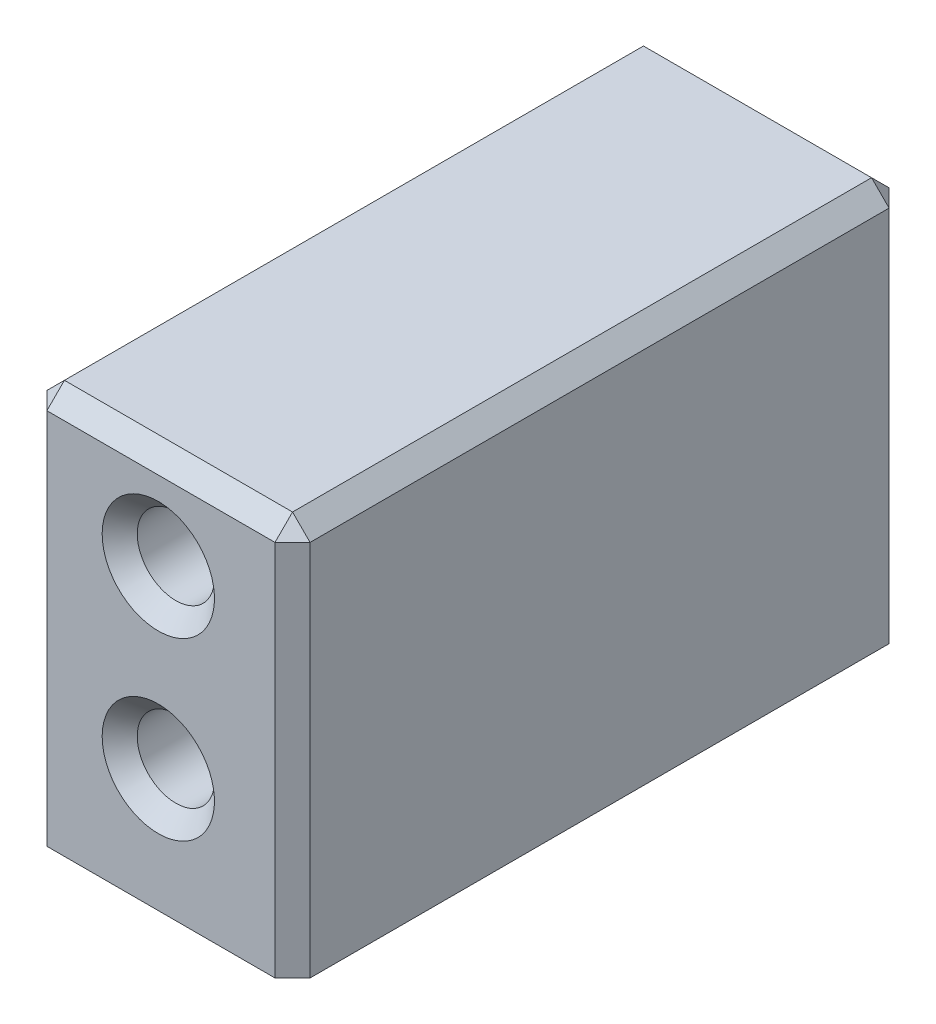
SolidWorks part; units mm, degrees
ref_plane "Front Plane" through (0, 0, 0) normal (0, 0, 1) x (1, 0, 0)
ref_plane "Top Plane" through (0, 0, 0) normal (0, 1, 0) x (1, 0, 0)
ref_plane "Right Plane" through (0, 0, 0) normal (1, 0, 0) x (0, 0, -1)
sketch "Sketch1" plane through (0, 0, 0) normal (0, 1, 0) x (1, 0, 0)
  line L0 (-41.5745, 21.3069) -> (-41.5745, -23.1431)
  line L9 (-41.5745, -23.1431) -> (-22.5245, -23.1431)
  line L10 (-22.5245, -23.1431) -> (-22.5245, 21.3069)
  line L11 (-22.5245, 21.3069) -> (-41.5745, 21.3069)
  dimension "D1" = 44.45
  dimension "D2" = 19.05
extrude "Boss-Extrude1" add sketch "Sketch1" along normal blind 28.575
sketch "Sketch3" plane through (0, 0, 23.1431) normal (0, 0, 1) x (1, 0, 0)
  line L1 (-41.5745, 0) -> (-22.5245, 0) construction
  line L3 (-41.5745, 28.575) -> (-41.5745, 0) construction
  circle A3 centre (-32.24, 34.29) radius 2.794
  circle A4 centre (-32.24, 21.59) radius 2.794
  circle A5 centre (-32.24, 8.89) radius 2.794
  dimension "D5" = 5.588
  dimension "D1" = 8.89
  dimension "D2" = 12.7
  dimension "D3" = 12.7
  dimension "D4" = 9.3345
extrude "Cut-Extrude2" cut sketch "Sketch3" against normal through all
chamfer "Chamfer2" distance 1.27 angle 45 12 edges at (-29.446, 8.89, 23.1431) (-29.446, 8.89, -21.3069) (-29.446, 21.59, 23.1431) (-29.446, 21.59, -21.3069) (-32.0495, 28.575, -21.3069) (-41.5745, 28.575, 0.9181) (-22.5245, 14.2875, -21.3069) (-22.5245, 28.575, 0.9181) (-22.5245, 14.2875, 23.1431) (-32.0495, 28.575, 23.1431) (-41.5745, 14.2875, 23.1431) (-41.5745, 14.2875, -21.3069)
